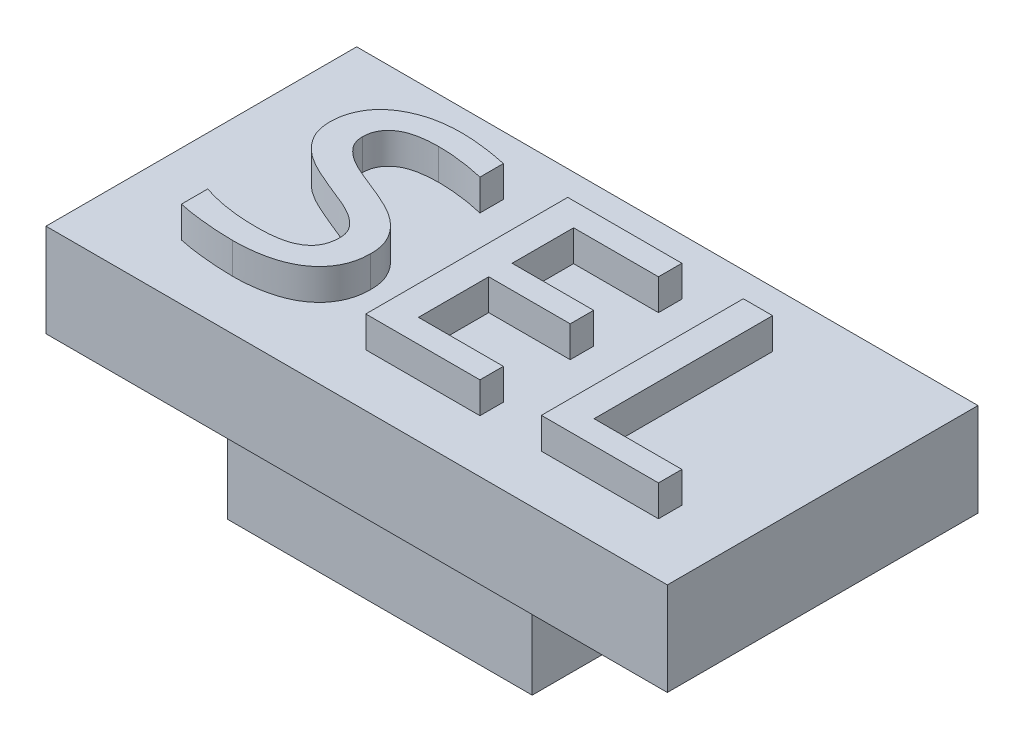
SolidWorks part; units mm, degrees
ref_plane "Front Plane" through (0, 0, 0) normal (0, 0, 1) x (1, 0, 0)
ref_plane "Top Plane" through (0, 0, 0) normal (0, 1, 0) x (1, 0, 0)
ref_plane "Right Plane" through (0, 0, 0) normal (1, 0, 0) x (0, 0, -1)
sketch "Sketch1" plane through (0, 0, 0) normal (0, 1, 0) x (1, 0, 0)
  line L1 (-10, -5) -> (10, -5)
  line L2 (-10, -5) -> (-10, 5)
  line L3 (-10, 5) -> (10, 5)
  line L4 (10, -5) -> (10, 5)
  line L5 (-10, -5) -> (10, 5) construction
  line L6 (-10, 5) -> (10, -5) construction
  point P0 (0, 0)
  dimension "D1" = 20
  dimension "D2" = 10
extrude "Boss-Extrude1" add sketch "Sketch1" along normal blind 3
sketch "Sketch2" plane through (0, 0, 0) normal (0, -1, 0) x (1, 0, 0)
  line L1 (-2.9, -2.25) -> (2.9, -2.25)
  line L2 (-2.9, -2.25) -> (-2.9, 2.25)
  line L3 (-2.9, 2.25) -> (2.9, 2.25)
  line L4 (2.9, -2.25) -> (2.9, 2.25)
  line L5 (-2.9, -2.25) -> (2.9, 2.25) construction
  line L6 (-2.9, 2.25) -> (2.9, -2.25) construction
  line L7 (-4.9, -4.25) -> (4.9, -4.25)
  line L8 (-4.9, -4.25) -> (-4.9, 4.25)
  line L9 (-4.9, 4.25) -> (4.9, 4.25)
  line L10 (4.9, -4.25) -> (4.9, 4.25)
  line L11 (-4.9, -4.25) -> (4.9, 4.25) construction
  line L12 (-4.9, 4.25) -> (4.9, -4.25) construction
  point P0 (0, 0)
  point P6 (0, 0)
  dimension "D1" = 4.5
  dimension "D2" = 5.8
  dimension "D3" = 2
  dimension "D4" = 2
extrude "Boss-Extrude2" add sketch "Sketch2" along normal blind 3
sketch "Sketch3" plane through (0, 3, 0) normal (0, 1, 0) x (1, 0, 0)
  text T0 "SEL" font "Consolas" height 6.5
  dimension "D1" = 8
  dimension "D2" = 3.3
extrude "Boss-Extrude3" add sketch "Sketch3" along normal blind 1
